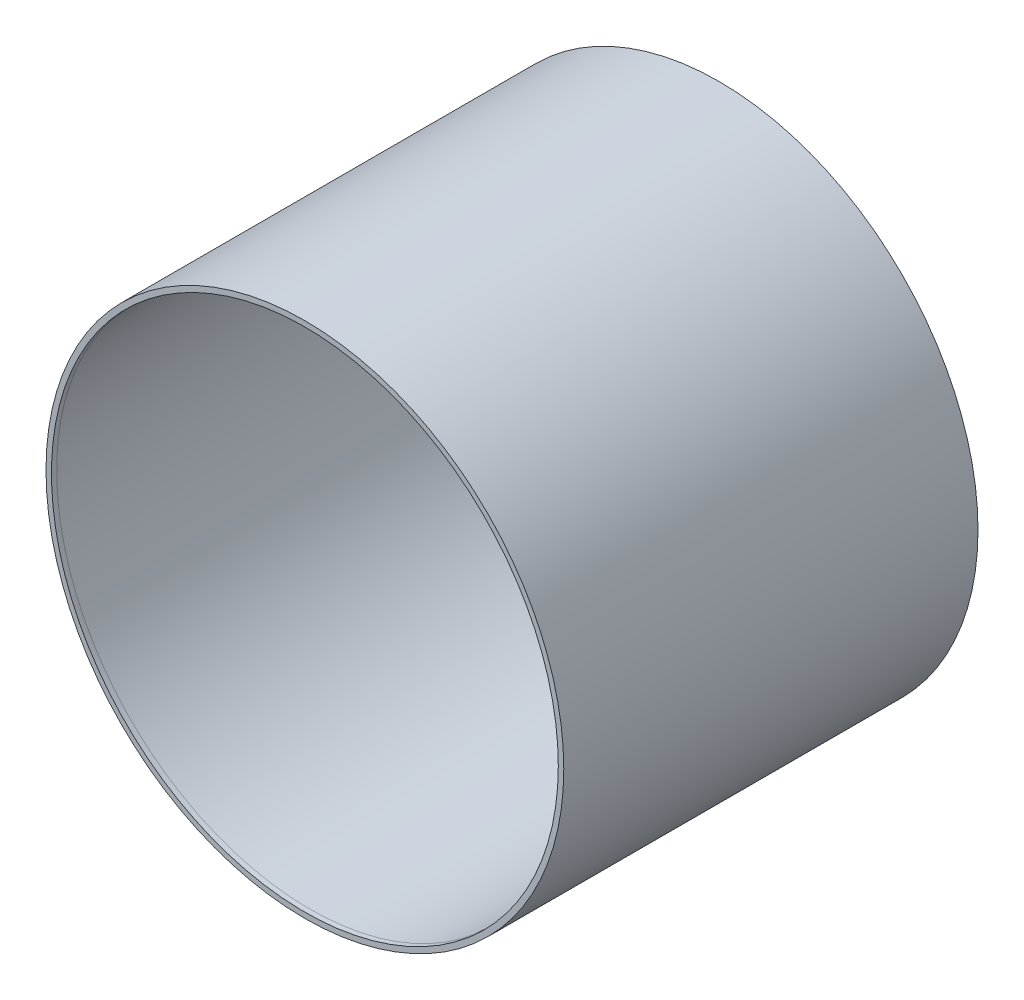
SolidWorks part; units mm, degrees
ref_plane "前视基准面" through (0, 0, 0) normal (0, 0, 1) x (1, 0, 0)
ref_plane "上视基准面" through (0, 0, 0) normal (0, 1, 0) x (1, 0, 0)
ref_plane "右视基准面" through (0, 0, 0) normal (1, 0, 0) x (0, 0, -1)
sketch "草图1" plane through (0, 0, 0) normal (0, 0, 1) x (1, 0, 0)
  circle A0 centre (0, 0) radius 50
  dimension "D1" = 100
extrude "凸台-拉伸1" add sketch "草图1" along normal blind 80
shell "抽壳1" thickness 1
sketch "草图2" plane through (0, 0, 80) normal (0, 0, 1) x (1, 0, 0)
  circle A0 centre (0, 0) radius 48.945
  dimension "D1" = 97.89
extrude "切除-拉伸1" cut sketch "草图2" against normal blind 1
